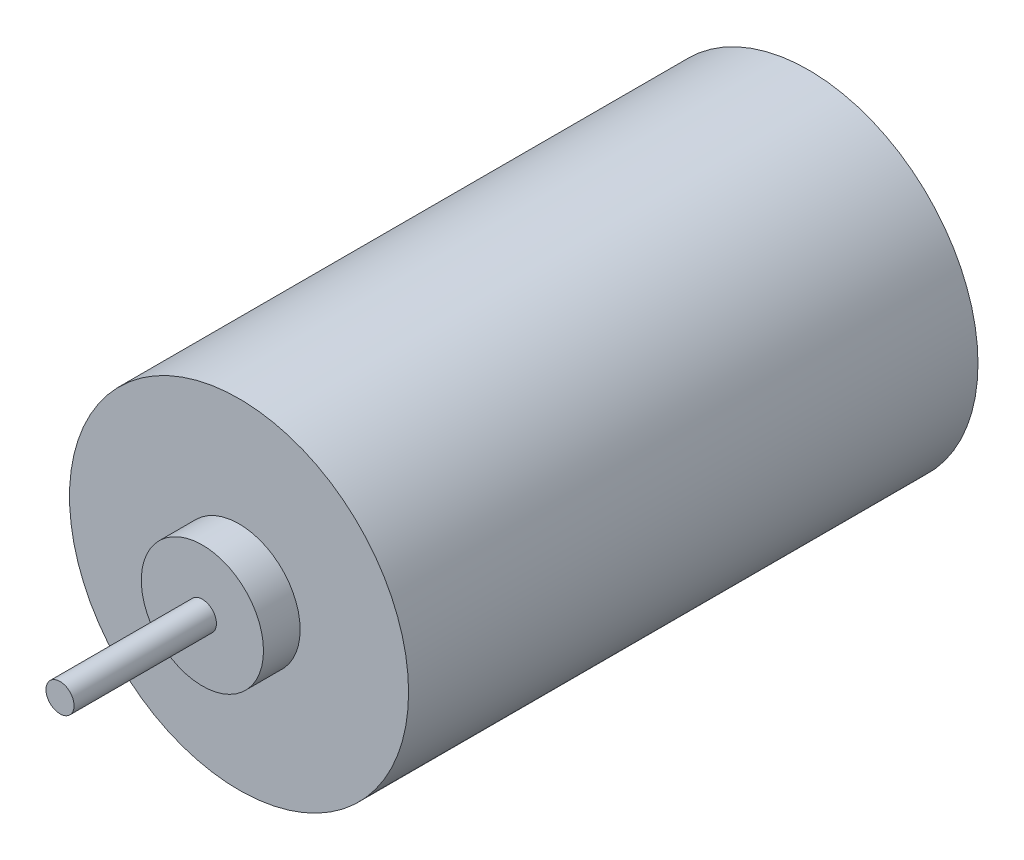
SolidWorks part; units mm, degrees
ref_plane "Front Plane" through (0, 0, 0) normal (0, 0, 1) x (1, 0, 0)
ref_plane "Top Plane" through (0, 0, 0) normal (0, 1, 0) x (1, 0, 0)
ref_plane "Right Plane" through (0, 0, 0) normal (1, 0, 0) x (0, 0, -1)
sketch "Sketch1" plane through (0, 0, 0) normal (0, 0, 1) x (1, 0, 0)
  circle A0 centre (0, 0) radius 13.875
  dimension "motor diameter " = 27.75
extrude "Boss-Extrude1" add sketch "Sketch1" along normal blind 46.6 contours A0
sketch "Sketch2" plane through (0, 0, 46.6) normal (0, 0, 1) x (1, 0, 0)
  circle A0 centre (0, 0) radius 5
  dimension "D1" = 10
extrude "Boss-Extrude2" add sketch "Sketch2" along normal blind 3
sketch "Sketch3" plane through (0, 0, 49.6) normal (0, 0, 1) x (1, 0, 0)
  circle A0 centre (0, 0) radius 1.15
  dimension "shaft_diameter" = 2.3
extrude "Boss-Extrude3" add sketch "Sketch3" along normal blind 11.65
